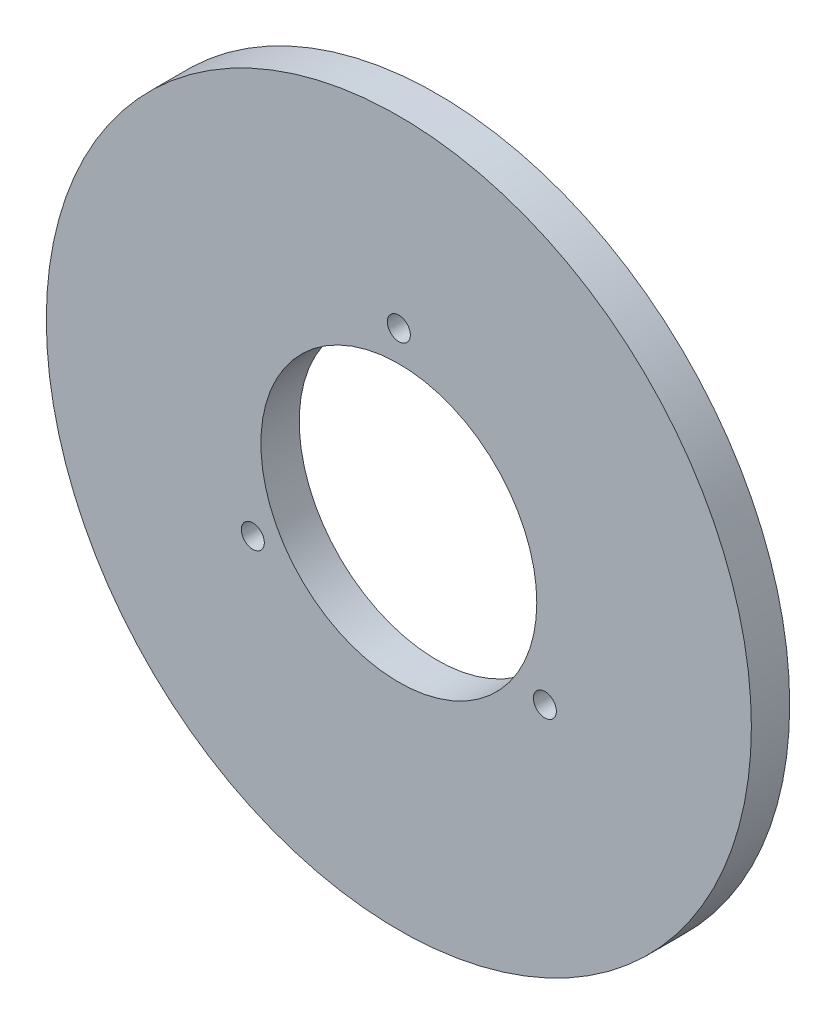
SolidWorks part; units mm, degrees
ref_plane "Front Plane" through (0, 0, 0) normal (0, 0, 1) x (1, 0, 0)
ref_plane "Top Plane" through (0, 0, 0) normal (0, 1, 0) x (1, 0, 0)
ref_plane "Right Plane" through (0, 0, 0) normal (1, 0, 0) x (0, 0, -1)
sketch "Sketch2" plane through (0, 0, 0) normal (0, 0, 1) x (1, 0, 0)
  circle A0 centre (0, 0) radius 46
  circle A2 centre (0, 0) radius 18
  point P13 (0, 0)
  dimension "D1" = 36
  dimension "D2" = 92
extrude "Boss-Extrude2" add sketch "Sketch2" along normal blind 5
sketch "Sketch4" plane through (0, 0, 5) normal (0, 0, 1) x (1, 0, 0)
  circle A0 centre (0, 0) radius 30
  circle A1 centre (0, 0) radius 18
  dimension "D1" = 60
extrude "Boss-Extrude3" [suppressed] add sketch "Sketch4" along normal blind 4
sketch "Sketch5" plane through (0, 0, 0) normal (0, 0, -1) x (-1, 0, 0)
  circle A0 centre (0, 0) radius 22 construction
  circle A1 centre (0, 22) radius 1.5
  circle A2 centre (19.0526, -11) radius 1.5
  circle A3 centre (-19.0526, -11) radius 1.5
  point P11 (0, 0)
  dimension "D1" = 44
  dimension "D2" = 3
  dimension "D3" = 3
extrude "Cut-Extrude1" cut sketch "Sketch5" against normal through all both and the other way through all
sketch "Sketch6" [suppressed] plane through (0, 0, 0) normal (1, 0, 0) x (0, 0, -1)
  line L0 (-5, 30) -> (-9, 30)
  line L1 (-9, 30) -> (-5, 46)
  line L2 (-5, 46) -> (-5, 30)
  line L3 (0, 0) -> (32.6688, 0) construction
revolve "Revolve1" [suppressed] add sketch "Sketch6" angle 16 mid plane about L3
pattern_circular "CirPattern1" [suppressed] count 6 over 360
